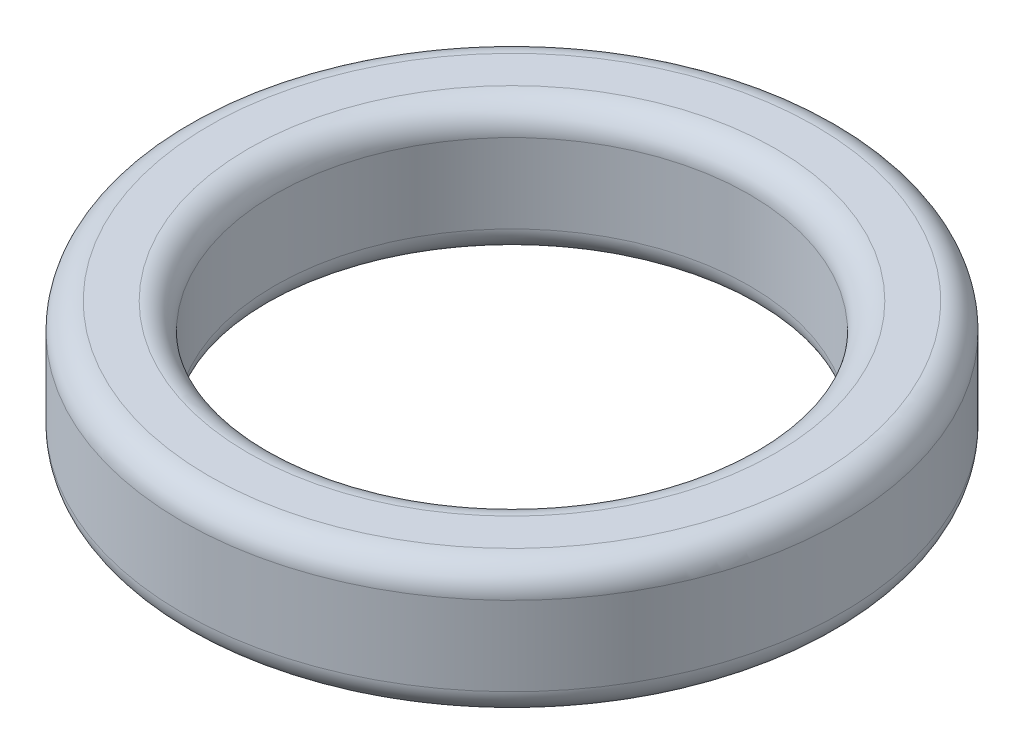
SolidWorks part; units mm, degrees
ref_plane "Front Plane" through (0, 0, 0) normal (0, 0, 1) x (1, 0, 0)
ref_plane "Top Plane" through (0, 0, 0) normal (0, 1, 0) x (1, 0, 0)
ref_plane "Right Plane" through (0, 0, 0) normal (1, 0, 0) x (0, 0, -1)
sketch "Sketch1" plane through (0, 0, 0) normal (0, 1, 0) x (1, 0, 0)
  circle A0 centre (0, 0) radius 2.286
  circle A1 centre (0, 0) radius 3.175
  dimension "D1" = 4.572
  dimension "D2" = 6.35
extrude "Boss-Extrude1" add sketch "Sketch1" along normal blind 1.27
fillet "Fillet2" radius 0.254 4 edges at (0, 0, 2.286) (0, 0, 3.175) (0, 1.27, 2.286) (0, 1.27, 3.175)
